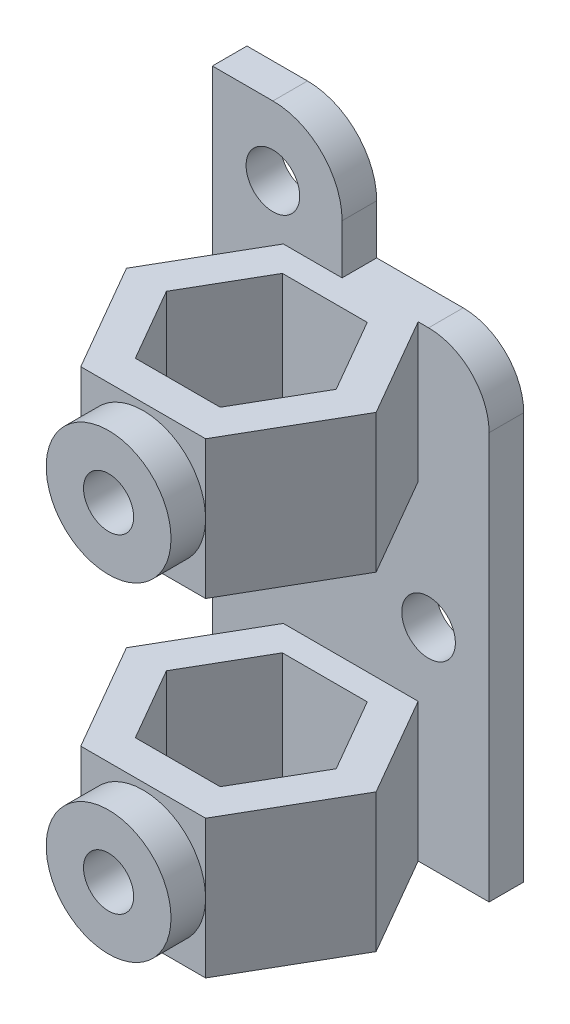
SolidWorks part; units mm, degrees
ref_plane "Front Plane" through (0, 0, 0) normal (0, 0, 1) x (1, 0, 0)
ref_plane "Top Plane" through (0, 0, 0) normal (0, 1, 0) x (1, 0, 0)
ref_plane "Right Plane" through (0, 0, 0) normal (1, 0, 0) x (0, 0, -1)
sketch "Sketch1" plane through (0, 0, 0) normal (0, 0, 1) x (1, 0, 0)
  line L1 (-8, 16.9303) -> (8, 16.9303)
  line L2 (-8, 16.9303) -> (-8, -16.9303)
  line L3 (-8, -16.9303) -> (8, -16.9303)
  line L4 (8, 16.9303) -> (8, -16.9303)
  circle A0 centre (-4.5, 12.9303) radius 1.55
  circle A1 centre (4.5, -4.9303) radius 1.55
  point P8 (0, 16.9303)
  point P10 (8, 0)
  dimension "D1" = 3.1
  dimension "D2" = 3.1
  dimension "D3" = 3.5
  dimension "D4" = 12.5
  dimension "D5" = 20
  dimension "D6" = 16
  dimension "D7" = 12
  dimension "D8" = 4
extrude "Boss-Extrude1" add sketch "Sketch1" along normal blind 2
sketch "Sketch2" plane through (0, -16.9303, 0) normal (0, -1, 0) x (1, 0, 0)
  line L0 (-8, 3.5) -> (8, 3.5) construction
  line L1 (-8, 2) -> (8, 2) construction
  line L2 (-2.4537, 3.5) -> (2.4537, 3.5)
  line L3 (2.4537, 3.5) -> (4.9075, 7.75)
  line L4 (4.9075, 7.75) -> (2.4537, 12)
  line L5 (2.4537, 12) -> (-2.4537, 12)
  line L6 (-2.4537, 12) -> (-4.9075, 7.75)
  line L7 (-4.9075, 7.75) -> (-2.4537, 3.5)
  line L8 (-3.6084, 14) -> (-7.2169, 7.75)
  line L9 (-7.2169, 7.75) -> (-3.8971, 2)
  line L11 (3.8971, 2) -> (7.2169, 7.75)
  line L12 (7.2169, 7.75) -> (3.6084, 14)
  line L13 (3.6084, 14) -> (-3.6084, 14)
  line L14 (-3.8971, 2) -> (3.8971, 2)
  line L15 (-7.2169, 7.75) -> (-3.6084, 1.5) construction
  line L16 (-3.6084, 1.5) -> (3.6084, 1.5) construction
  line L17 (3.6084, 1.5) -> (7.2169, 7.75) construction
  line L18 (8, 2) -> (8, 0) construction
  line L19 (-8, 2) -> (-8, 0) construction
  circle A0 centre (0, 7.75) radius 4.25 construction
  dimension "D2" = 8.5
  dimension "D1" = 1.5
  dimension "D3" = 2
extrude "Boss-Extrude2" add sketch "Sketch2" against normal blind 8
sketch "Sketch3" plane through (0, -8.9303, 0) normal (0, 1, 0) x (1, 0, 0)
  line L6 (-3.6084, -14) -> (3.6084, -14)
  line L7 (3.6084, -14) -> (7.2169, -7.75)
  line L8 (7.2169, -7.75) -> (3.8971, -2)
  line L9 (3.8971, -2) -> (-3.8971, -2)
  line L10 (-3.8971, -2) -> (-7.2169, -7.75)
  line L11 (-7.2169, -7.75) -> (-3.6084, -14)
  line L12 (-3.6084, -14) -> (3.6084, -14)
  line L13 (3.6084, -14) -> (7.2169, -7.75)
  line L14 (7.2169, -7.75) -> (3.8971, -2)
  line L15 (3.8971, -2) -> (-3.8971, -2)
  line L16 (-3.8971, -2) -> (-7.2169, -7.75)
  line L17 (-7.2169, -7.75) -> (-3.6084, -14)
  line L19 (-4.9075, -7.75) -> (-2.4537, -12)
  line L20 (-2.4537, -3.5) -> (-4.9075, -7.75)
  line L21 (2.4537, -3.5) -> (-2.4537, -3.5)
  line L22 (4.9075, -7.75) -> (2.4537, -3.5)
  line L23 (2.4537, -12) -> (4.9075, -7.75)
  line L24 (-2.4537, -12) -> (2.4537, -12)
  line L25 (-4.9075, -7.75) -> (-2.4537, -12)
  line L26 (-2.4537, -3.5) -> (-4.9075, -7.75)
  line L27 (2.4537, -3.5) -> (-2.4537, -3.5)
  line L28 (4.9075, -7.75) -> (2.4537, -3.5)
  line L29 (2.4537, -12) -> (4.9075, -7.75)
  line L30 (-2.4537, -12) -> (2.4537, -12)
  dimension "D1" = 0
  dimension "D2" = 0
extrude "Boss-Extrude3" add sketch "Sketch3" along normal blind 8 from offset 11
sketch "Sketch4" plane through (0, 0, 14) normal (0, 0, 1) x (1, 0, 0)
  line L0 (3.6084, 10.0697) -> (-3.6084, 2.0697) construction
  line L1 (-3.6084, 2.0697) -> (3.6084, 2.0697) construction
  line L2 (3.6084, 2.0697) -> (-3.6084, 10.0697) construction
  line L3 (-3.6084, -8.9303) -> (3.6084, -16.9303) construction
  line L4 (3.6084, -16.9303) -> (-3.6084, -16.9303) construction
  line L5 (-3.6084, -16.9303) -> (3.6084, -8.9303) construction
  circle A0 centre (0, -12.9303) radius 1.45
  circle A1 centre (0, 6.0697) radius 1.45
  dimension "D1" = 2.9
  dimension "D2" = 2.9
extrude "Cut-Extrude1" cut sketch "Sketch4" against normal up to next
sketch "Sketch5" plane through (0, 0, 2) normal (0, 0, 1) x (1, 0, 0)
  line L0 (-0.5, 12.9303) -> (-0.5, 10.0697)
  line L1 (3.8971, 10.0697) -> (-3.8971, 10.0697) construction
  line L2 (8, 10.0697) -> (-0.5, 10.0697)
  line L4 (8, 10.0697) -> (8, 16.9303)
  line L5 (-4.5, 16.9303) -> (8, 16.9303)
  arc A0 (-0.5, 12.9303) -> (-4.5, 16.9303) centre (-4.5, 12.9303) ccw
  dimension "D1" = 8
extrude "Cut-Extrude2" cut sketch "Sketch5" against normal up to next
fillet "Fillet1" radius 3.5 1 edges at (8, 10.0697, 1)
sketch "Sketch6" plane through (0, 0, 14) normal (0, 0, 1) x (1, 0, 0)
  line L0 (3.6084, 10.0697) -> (3.6084, 2.0697) construction
  line L1 (3.6084, -8.9303) -> (3.6084, -16.9303) construction
  circle A0 centre (0, 6.0697) radius 3.6084
  circle A1 centre (0, 6.0697) radius 1.45
  circle A2 centre (0, -12.9303) radius 3.6084
  circle A3 centre (0, -12.9303) radius 1.45
  circle A4 centre (0, 6.0697) radius 1.45 construction
  circle A5 centre (0, -12.9303) radius 1.45 construction
extrude "Boss-Extrude4" add sketch "Sketch6" along normal blind 2
